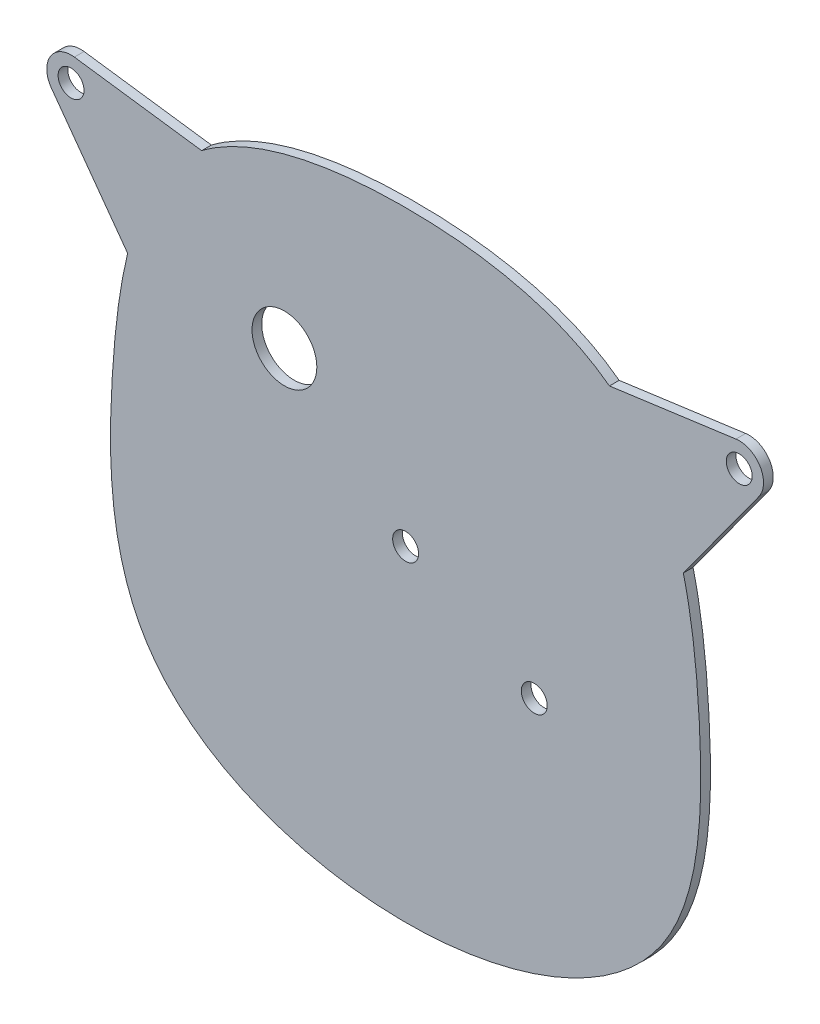
SolidWorks part; units mm, degrees
ref_plane "前视基准面" through (0, 0, 0) normal (0, 0, 1) x (1, 0, 0)
ref_plane "上视基准面" through (0, 0, 0) normal (0, 1, 0) x (1, 0, 0)
ref_plane "右视基准面" through (0, 0, 0) normal (1, 0, 0) x (0, 0, -1)
sketch "草图1" plane through (0, 0, 0) normal (0, 0, 1) x (1, 0, 0)
  line L0 (-62.9468, 79.3062) -> (-102.216, 84.6673)
  line L1 (-109.297, 72.8263) -> (-85.7736, 40.4662)
  line L2 (108.9501, 72.8263) -> (85.6486, 40.7715)
  line L3 (62.8512, 79.3405) -> (101.869, 84.6673)
  circle A0 centre (-0.025, 5.0604) radius 4
  circle A1 centre (39.6608, -15.6887) radius 4
  arc A2 (-102.216, 84.6673) -> (-109.297, 72.8263) centre (-103.2305, 77.2362) ccw
  circle A3 centre (-103.2305, 77.2362) radius 4
  circle A4 centre (102.8835, 77.2362) radius 4
  circle A5 centre (-37.4126, 39.2362) radius 10
  arc A6 (108.9501, 72.8263) -> (101.869, 84.6673) centre (102.8835, 77.2362) ccw
  spline S0 degree 3 poles (85.6486, 40.7715) (85.7519, 40.3526) (87.358, 33.6933) (88.9821, 23.4613) (90.1889, 10.1127) (90.9984, -3.2398) (91.224, -19.8199) (89.4578, -35.6085) (86.2894, -47.3833) (82.8901, -55.6783) (78.2934, -63.3251) (70.5393, -72.4184) (58.2669, -81.7179) (40.5056, -89.6395) (20.7415, -94.3834) (-0.025, -95.9677) (-20.7916, -94.3834) (-40.5557, -89.6395) (-58.317, -81.7179) (-70.5893, -72.4184) (-78.3435, -63.3251) (-82.9401, -55.6783) (-86.3394, -47.3833) (-89.5078, -35.6085) (-91.2741, -19.8199) (-91.0485, -3.2398) (-90.239, 10.1127) (-89.0322, 23.4613) (-87.425, 33.5866) (-85.8511, 40.1485) (-85.7736, 40.4662) knots 1.185395 1.185395 1.185395 1.185395 1.1875 1.21875 1.234375 1.25 1.28125 1.3125 1.328125 1.34375 1.359375 1.375 1.40625 1.4375 1.46875 1.5 1.53125 1.5625 1.59375 1.625 1.640625 1.65625 1.671875 1.6875 1.71875 1.75 1.765625 1.78125 1.8125 1.814094 1.814094 1.814094 1.814094
  spline S1 degree 3 poles (-62.9468, 79.3062) (-60.97, 80.7991) (-53.8783, 85.4443) (-39.9164, 91.1117) (-20.475, 94.8529) (-6.8417, 95.5604) (-0.025, 95.5604) (6.7916, 95.5604) (20.4249, 94.8529) (39.8664, 91.1117) (53.8098, 85.4518) (60.8879, 80.8201) (62.8512, 79.3405) knots 0.89321 0.89321 0.89321 0.89321 0.90625 0.9375 0.96875 1 1 1 1.03125 1.0625 1.09375 1.10669 1.10669 1.10669 1.10669
  dimension "D2" = 8
  dimension "D3" = 8
  dimension "D4" = 8
  dimension "D1" = 206.114
extrude "凸台-拉伸1" add sketch "草图1" along normal blind 3
